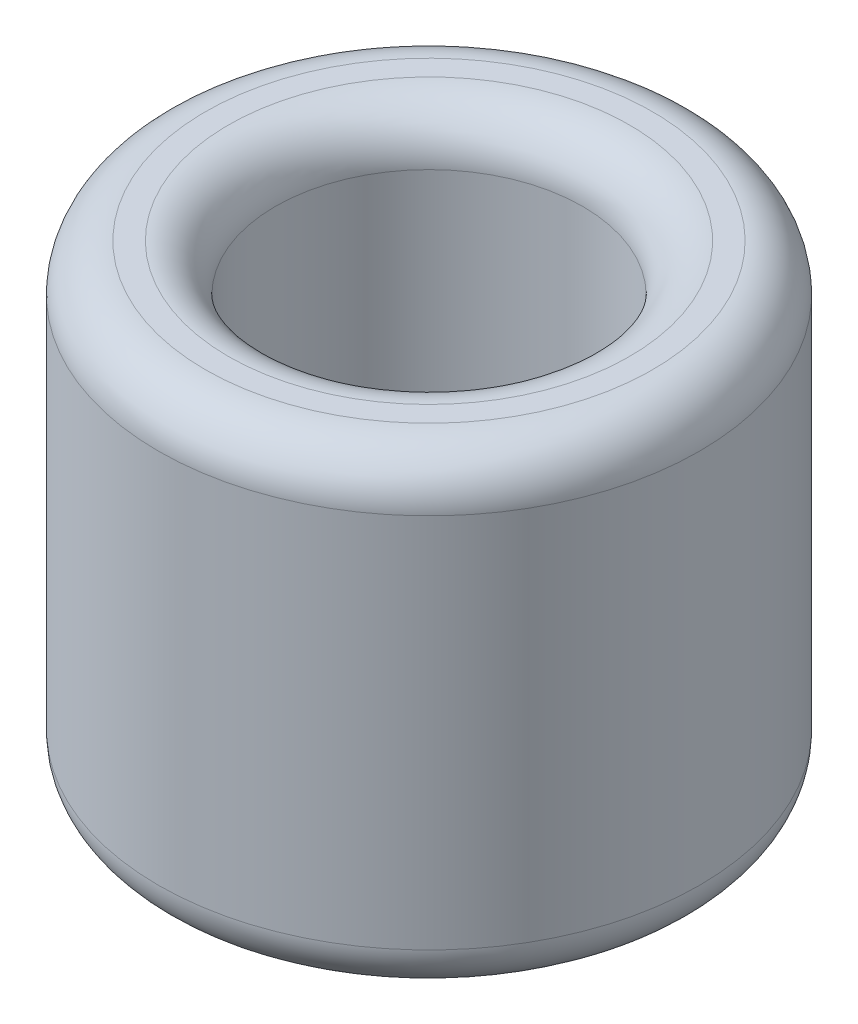
SolidWorks part; units mm, degrees
ref_plane "Front Plane" through (0, 0, 0) normal (0, 0, 1) x (1, 0, 0)
ref_plane "Top Plane" through (0, 0, 0) normal (0, 1, 0) x (1, 0, 0)
ref_plane "Right Plane" through (0, 0, 0) normal (1, 0, 0) x (0, 0, -1)
sketch "Sketch1" plane through (0, 0, 0) normal (0, 1, 0) x (1, 0, 0)
  circle A0 centre (0, 0) radius 14.6221
extrude "Boss-Extrude2" add sketch "Sketch1" along normal blind 25.4
sketch "Sketch2" plane through (0, 25.4, 0) normal (0, 1, 0) x (1, 0, 0)
  circle A0 centre (0, 0) radius 8.3
extrude "Cut-Extrude1" cut sketch "Sketch2" against normal blind 25.4
fillet "Fillet1" radius 2.54 4 edges at (0, 0, 8.3) (0, 25.4, 8.3) (0, 0, 14.6221) (0, 25.4, 14.6221)
